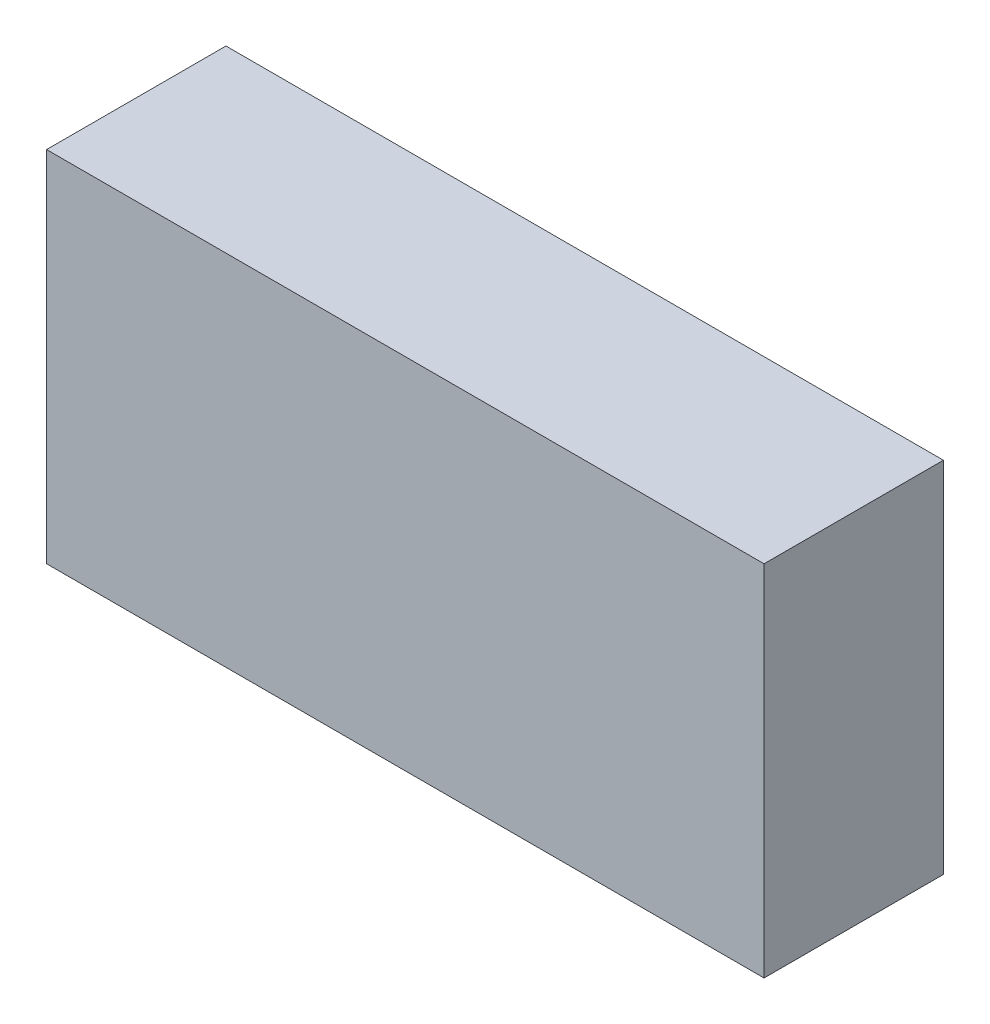
SolidWorks part; units mm, degrees
ref_plane "Front Plane" through (0, 0, 0) normal (0, 0, 1) x (1, 0, 0)
ref_plane "Top Plane" through (0, 0, 0) normal (0, 1, 0) x (1, 0, 0)
ref_plane "Right Plane" through (0, 0, 0) normal (1, 0, 0) x (0, 0, -1)
sketch "Sketch1" plane through (0, 0, 0) normal (0, 0, 1) x (1, 0, 0)
  line L0 (-20, -10) -> (20, -10)
  line L1 (20, -10) -> (20, 10)
  line L2 (20, 10) -> (-20, 10)
  line L3 (-20, 10) -> (-20, -10)
  dimension "D1" = 40
  dimension "D2" = 20
extrude "Boss-Extrude1" add sketch "Sketch1" along normal blind 10
sketch "Sketch2" plane through (0, 0, 0) normal (0, 0, 1) x (1, 0, 0)
  line L0 (-18, -5) -> (-12, -5)
  line L1 (-12, -5) -> (-12, 1)
  line L2 (-12, 1) -> (-18, 1)
  line L3 (-18, 1) -> (-18, -5)
  dimension "D1" = 6
  dimension "D2" = 6
extrude "Boss-Extrude2" add sketch "Sketch2" along normal blind 5
